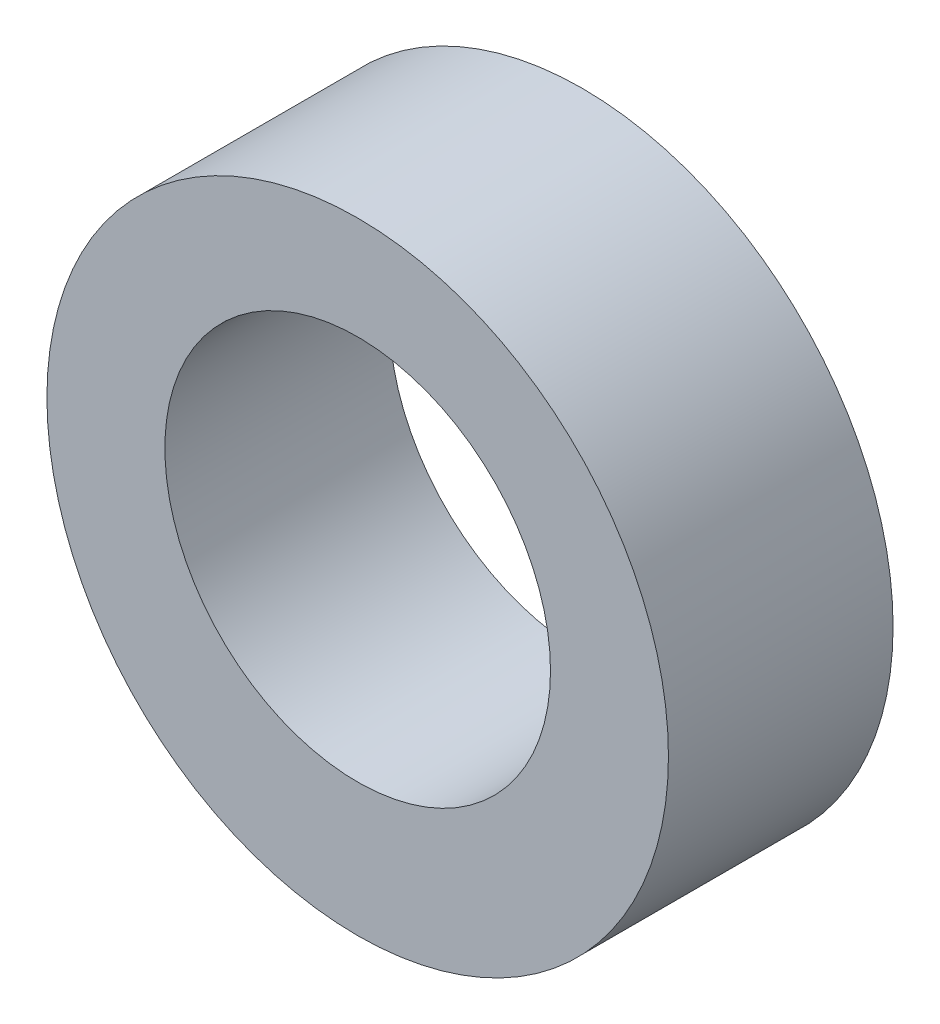
SolidWorks part; units mm, degrees
ref_plane "Front Plane" through (0, 0, 0) normal (0, 0, 1) x (1, 0, 0)
ref_plane "Top Plane" through (0, 0, 0) normal (0, 1, 0) x (1, 0, 0)
ref_plane "Right Plane" through (0, 0, 0) normal (1, 0, 0) x (0, 0, -1)
sketch "Sketch1" plane through (0, 0, 0) normal (0, 0, 1) x (1, 0, 0)
  circle A0 centre (0, 14.9368) radius 69.174
extrude "Boss-Extrude1" add sketch "Sketch1" along normal blind 50
sketch "Sketch4" plane through (0, 0, 50) normal (0, 0, 1) x (1, 0, 0)
  circle A0 centre (0, 18.2876) radius 42.9183
extrude "Cut-Extrude1" cut sketch "Sketch4" against normal blind 50
